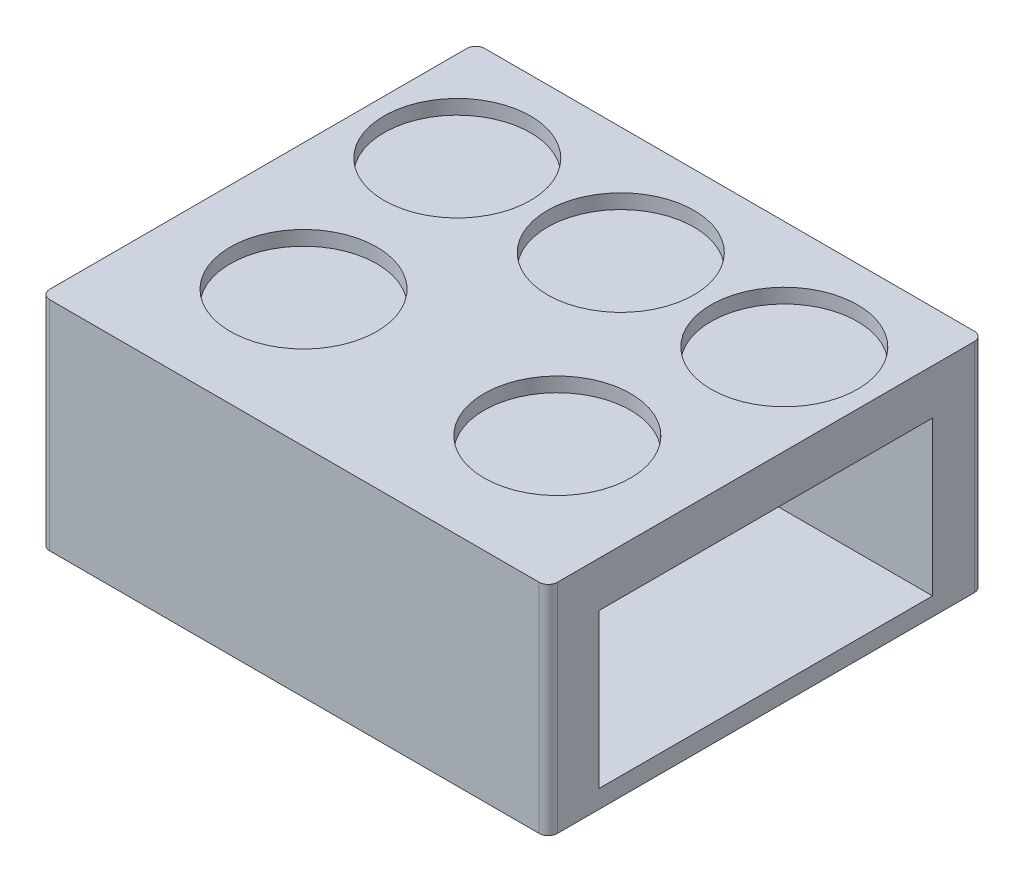
SolidWorks part; units mm, degrees
ref_plane "Front Plane" through (0, 0, 0) normal (0, 0, 1) x (1, 0, 0)
ref_plane "Top Plane" through (0, 0, 0) normal (0, 1, 0) x (1, 0, 0)
ref_plane "Right Plane" through (0, 0, 0) normal (1, 0, 0) x (0, 0, -1)
sketch "Sketch1" plane through (0, 0, 0) normal (0, 1, 0) x (1, 0, 0)
  line L3 (0, 120) -> (-135, 120)
  line L4 (-140, 115) -> (-140, -115)
  line L5 (-135, -120) -> (135, -120)
  line L6 (140, -115) -> (140, 115)
  line L7 (135, 120) -> (0, 120)
  arc A0 (140, 115) -> (135, 120) centre (135, 115) ccw
  arc A1 (135, -120) -> (140, -115) centre (135, -115) ccw
  arc A2 (-140, -115) -> (-135, -120) centre (-135, -115) ccw
  arc A3 (-135, 120) -> (-140, 115) centre (-135, 115) ccw
  dimension "D1" = 5
  dimension "D2" = 240
  dimension "D3" = 280
extrude "Boss-Extrude1" add sketch "Sketch1" along normal blind 120
sketch "Sketch2" plane through (140, 0, 0) normal (1, 0, 0) x (0, 0, -1)
  line L0 (0, 120) -> (0, 0) construction
  line L1 (-115, 120) -> (115, 120) construction
  line L2 (-115, 0) -> (115, 0) construction
  line L3 (-115, 60) -> (115, 60) construction
  line L4 (-115, 120) -> (-115, 0) construction
  line L5 (115, 120) -> (115, 0) construction
  line L8 (-92, 95) -> (-92, 10)
  line L14 (-92, 10) -> (92, 10)
  line L15 (92, 10) -> (92, 95)
  line L16 (-92, 95) -> (92, 95)
extrude "Cut-Extrude1" cut sketch "Sketch2" against normal blind 370
sketch "Sketch3" plane through (0, 120, 0) normal (0, 1, 0) x (1, 0, 0)
  line L0 (0, 120) -> (0, -120) construction
  line L1 (135, 120) -> (-135, 120) construction
  line L2 (-135, -120) -> (135, -120) construction
  line L3 (-140, 0) -> (140, 0) construction
  line L4 (-140, 115) -> (-140, -115) construction
  line L5 (140, -115) -> (140, 115) construction
  circle A0 centre (70, -45) radius 40.4
  circle A1 centre (-70, -45) radius 40.4
  circle A2 centre (0, 60) radius 40.4
  circle A3 centre (-90.2, 60) radius 40.4
  circle A4 centre (90.2, 60) radius 40.4
  dimension "D1" = 80.8
  dimension "D2" = 80.8
  dimension "D3" = 80.8
  dimension "D4" = 80.8
extrude "Cut-Extrude2" cut sketch "Sketch3" against normal blind 8
